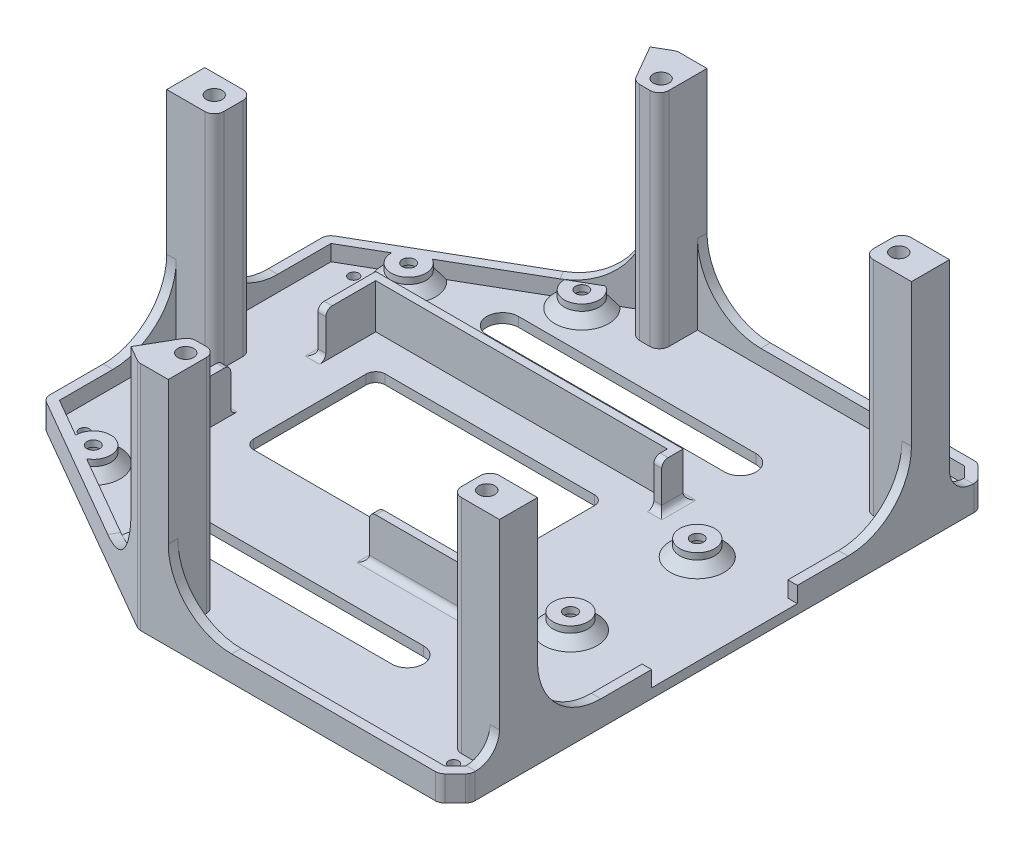
SolidWorks part; units mm, degrees
material "ABS"
ref_plane "Front Plane" through (0, 0, 0) normal (0, 0, 1) x (1, 0, 0)
ref_plane "Top Plane" through (0, 0, 0) normal (0, 1, 0) x (1, 0, 0)
ref_plane "Right Plane" through (0, 0, 0) normal (1, 0, 0) x (0, 0, -1)
sketch "Sketch1" plane through (0, 0, 0) normal (0, 1, 0) x (1, 0, 0)
  line L0 (-50, 85) -> (-120, 44.5855)
  line L1 (-50, -85) -> (50, -85)
  line L2 (-50, -85) -> (-50, 85) construction
  line L3 (-50, 85) -> (50, 85)
  line L4 (50, -85) -> (50, 85)
  line L5 (-50, -85) -> (50, 85) construction
  line L6 (-50, 85) -> (50, -85) construction
  line L7 (-120, 44.5855) -> (-120, -44.5855)
  line L8 (-120, -44.5855) -> (-50, -85)
  line L9 (-120, 0) -> (-35, 0) construction
  line L10 (-85, 64.7927) -> (-47.5919, 0) construction
  line L11 (-47.5919, 0) -> (-85, -64.7927) construction
  circle A0 centre (-35, 0) radius 85 construction
  point P0 (0, 0)
  dimension "D5" = 120
  dimension "D1" = 170
  dimension "D2" = 100
  dimension "D3" = 170
  dimension "D4" = 85
extrude "Boss-Extrude1" add sketch "Sketch1" along normal blind 3
chamfer "Chamfer1" distance 5 angle 45 2 edges at (50, 1.5, 85) (50, 1.5, -85)
fillet "Fillet1" radius 3 8 edges at (50, 1.5, -80) (45, 1.5, -85) (-50, 1.5, -85) (-50, 1.5, 85) (-120, 1.5, -44.5855) (-120, 1.5, 44.5855) (50, 1.5, 80) (45, 1.5, 85)
sketch "Sketch3" plane through (0, 3, 0) normal (0, 1, 0) x (1, 0, 0)
  line L0 (-117, 42.8534) -> (-117, -42.8534)
  line L1 (-117, -42.8534) -> (-49.1962, -82)
  line L2 (-49.1962, -82) -> (43.7574, -82)
  line L3 (43.7574, -82) -> (47, -78.7574)
  line L4 (47, -78.7574) -> (47, 78.7574)
  line L5 (47, 78.7574) -> (43.7574, 82)
  line L6 (43.7574, 82) -> (-49.1962, 82)
  line L7 (-49.1962, 82) -> (-117, 42.8534)
  line L8 (50, -78.7574) -> (50, 78.7574)
  line L9 (49.1213, 80.8787) -> (45.8787, 84.1213)
  line L10 (43.7574, 85) -> (-49.1962, 85)
  line L11 (-50.6962, 84.5981) -> (-118.5, 45.4515)
  line L12 (-120, 42.8534) -> (-120, -42.8534)
  line L13 (-118.5, -45.4515) -> (-50.6962, -84.5981)
  line L14 (-49.1962, -85) -> (43.7574, -85)
  line L15 (45.8787, -84.1213) -> (49.1213, -80.8787)
  line L16 (50, -78.7574) -> (50, 78.7574)
  line L17 (49.1213, 80.8787) -> (45.8787, 84.1213)
  line L18 (43.7574, 85) -> (-49.1962, 85)
  line L19 (-50.6962, 84.5981) -> (-118.5, 45.4515)
  line L20 (-120, 42.8534) -> (-120, -42.8534)
  line L21 (-118.5, -45.4515) -> (-50.6962, -84.5981)
  line L22 (-49.1962, -85) -> (43.7574, -85)
  line L23 (45.8787, -84.1213) -> (49.1213, -80.8787)
  arc A0 (-117, -42.8534) -> (-117, -42.8534) centre (-117, -42.8534) ccw
  arc A1 (-49.1962, -82) -> (-49.1962, -82) centre (-49.1962, -82) ccw
  arc A2 (43.7574, -82) -> (43.7574, -82) centre (43.7574, -82) ccw
  arc A3 (47, -78.7574) -> (47, -78.7574) centre (47, -78.7574) ccw
  arc A4 (47, 78.7574) -> (47, 78.7574) centre (47, 78.7574) ccw
  arc A5 (43.7574, 82) -> (43.7574, 82) centre (43.7574, 82) ccw
  arc A6 (-49.1962, 82) -> (-49.1962, 82) centre (-49.1962, 82) ccw
  arc A7 (-117, 42.8534) -> (-117, 42.8534) centre (-117, 42.8534) ccw
  arc A8 (50, 78.7574) -> (49.1213, 80.8787) centre (47, 78.7574) ccw
  arc A9 (45.8787, 84.1213) -> (43.7574, 85) centre (43.7574, 82) ccw
  arc A10 (-49.1962, 85) -> (-50.6962, 84.5981) centre (-49.1962, 82) ccw
  arc A11 (-118.5, 45.4515) -> (-120, 42.8534) centre (-117, 42.8534) ccw
  arc A12 (-120, -42.8534) -> (-118.5, -45.4515) centre (-117, -42.8534) ccw
  arc A13 (-50.6962, -84.5981) -> (-49.1962, -85) centre (-49.1962, -82) ccw
  arc A14 (43.7574, -85) -> (45.8787, -84.1213) centre (43.7574, -82) ccw
  arc A15 (49.1213, -80.8787) -> (50, -78.7574) centre (47, -78.7574) ccw
  arc A16 (50, 78.7574) -> (49.1213, 80.8787) centre (47, 78.7574) ccw
  arc A17 (45.8787, 84.1213) -> (43.7574, 85) centre (43.7574, 82) ccw
  arc A18 (-49.1962, 85) -> (-50.6962, 84.5981) centre (-49.1962, 82) ccw
  arc A19 (-118.5, 45.4515) -> (-120, 42.8534) centre (-117, 42.8534) ccw
  arc A20 (-120, -42.8534) -> (-118.5, -45.4515) centre (-117, -42.8534) ccw
  arc A21 (-50.6962, -84.5981) -> (-49.1962, -85) centre (-49.1962, -82) ccw
  arc A22 (43.7574, -85) -> (45.8787, -84.1213) centre (43.7574, -82) ccw
  arc A23 (49.1213, -80.8787) -> (50, -78.7574) centre (47, -78.7574) ccw
  dimension "D1" = 0
  dimension "D2" = 3
extrude "Boss-Extrude2" add sketch "Sketch3" along normal blind 5
sketch "Sketch9" plane through (0, 3, 0) normal (0, 1, 0) x (1, 0, 0)
  line L0 (38, 85) -> (38, 76) construction
  line L1 (43.7574, 85) -> (-49.1962, 85) construction
  line L2 (41, 73) -> (50, 73) construction
  line L3 (50, -78.7574) -> (50, 78.7574) construction
  line L4 (50, 73) -> (50, 78.7574) construction
  line L5 (49.1213, 80.8787) -> (45.8787, 84.1213) construction
  line L6 (43.7574, 85) -> (38, 85) construction
  line L7 (-55.3827, 81.8923) -> (-49.3827, 71.5)
  line L8 (-46.7846, 70) -> (-43.5167, 70)
  line L9 (49.1213, 80.8787) -> (45.8787, 84.1213) construction
  line L10 (-120, 38.2457) -> (-108, 38.2457) construction
  line L11 (-120, 42.8534) -> (-120, -42.8534) construction
  line L12 (-105, 41.2457) -> (-105, 53.2457) construction
  line L13 (-50.6962, 84.5981) -> (-118.5, 45.4515) construction
  line L14 (-105, 53.2457) -> (-118.5, 45.4515) construction
  line L15 (-120, 42.8534) -> (-120, 38.2457) construction
  line L16 (-120, 0) -> (50, 0) construction
  line L26 (-40.5167, 73) -> (-40.5167, 85)
  line L27 (43.7574, 85) -> (-49.1962, 85) construction
  line L28 (-40.5167, 85) -> (-49.1962, 85)
  line L29 (-50.6962, 84.5981) -> (-55.3827, 81.8923)
  line L30 (-120, 0) -> (-105, 0)
  line L31 (-105, -3) -> (-105, 3)
  line L32 (-108, 6) -> (-120, 6)
  line L33 (-120, 6) -> (-120, -6)
  line L34 (50, 71) -> (38, 71)
  line L35 (35, 68) -> (35, 62)
  line L36 (38, 59) -> (50, 59)
  line L37 (50, 59) -> (50, 71)
  line L38 (38, -59) -> (50, -59)
  line L39 (35, -68) -> (35, -62)
  line L40 (50, -71) -> (38, -71)
  line L41 (50, -59) -> (50, -71)
  line L42 (-40.5167, -85) -> (-49.1962, -85)
  line L43 (-40.5167, -73) -> (-40.5167, -85)
  line L44 (-46.7846, -70) -> (-43.5167, -70)
  line L45 (-55.3827, -81.8923) -> (-49.3827, -71.5)
  line L46 (-50.6962, -84.5981) -> (-55.3827, -81.8923)
  line L47 (-108, -6) -> (-120, -6)
  arc A0 (-49.1962, 85) -> (-50.6962, 84.5981) centre (-49.1962, 82) ccw
  arc A1 (45.8787, 84.1213) -> (43.7574, 85) centre (43.7574, 82) ccw construction
  arc A2 (50, 78.7574) -> (49.1213, 80.8787) centre (47, 78.7574) ccw construction
  arc A3 (-118.5, 45.4515) -> (-120, 42.8534) centre (-117, 42.8534) ccw construction
  arc A4 (-105, 41.2457) -> (-108, 38.2457) centre (-108, 41.2457) cw construction
  arc A5 (38, 76) -> (41, 73) centre (41, 76) ccw construction
  arc A11 (-43.5167, 70) -> (-40.5167, 73) centre (-43.5167, 73) ccw
  arc A12 (-49.3827, 71.5) -> (-46.7846, 70) centre (-46.7846, 73) ccw
  arc A13 (-105, 3) -> (-108, 6) centre (-108, 3) ccw
  arc A14 (35, 62) -> (38, 59) centre (38, 62) ccw
  arc A15 (38, 71) -> (35, 68) centre (38, 68) ccw
  arc A16 (35, -62) -> (38, -59) centre (38, -62) cw
  arc A17 (38, -71) -> (35, -68) centre (38, -68) cw
  arc A18 (-43.5167, -70) -> (-40.5167, -73) centre (-43.5167, -73) cw
  arc A19 (-49.3827, -71.5) -> (-46.7846, -70) centre (-46.7846, -73) cw
  arc A20 (-49.1962, -85) -> (-50.6962, -84.5981) centre (-49.1962, -82) cw
  arc A21 (-105, -3) -> (-108, -6) centre (-108, -3) cw
  point P19 (45, 85)
  point P30 (-105, 38.2457)
  point P47 (-40.5167, 70)
  point P50 (-48.5167, 70)
  point P53 (-105, 6)
  point P58 (50, 56.4054)
  point P61 (35, 59)
  point P64 (35, 71)
  line M20 (43.7574, 82) -> (-49.1962, 82)
  line M21 (-49.1962, 82) -> (-117, 42.8534)
  line M22 (-117, 42.8534) -> (-117, -42.8534)
  line M23 (-117, -42.8534) -> (-49.1962, -82)
  line M31 (-49.1962, -82) -> (43.7574, -82)
  line M33 (47, -78.7574) -> (47, 78.7574)
  dimension "D2" = 3
  dimension "D3" = 3
  dimension "D4" = 3
  dimension "D6" = 3
  dimension "D7" = 3
  dimension "D10" = 3
  dimension "D11" = 3
  dimension "D14" = 3
  dimension "D18" = 3
  dimension "D1" = 12
  dimension "D5" = 15
  dimension "D8" = 15
  dimension "D9" = 8
  dimension "D12" = 6
  dimension "D13" = 15
  dimension "D15" = 12
  dimension "D16" = 15
  dimension "D17" = 14
extrude "Boss-Extrude5" add sketch "Sketch9" along normal blind 70 contours L31 A13 L32 L30 M22 | A21 L31 L30 L47 M22 | A19 L45 L43 A18 L44 M23 M31 | A20 L42 L43 L45 L46 M31 M23 | A17 L40 L38 A16 L39 M33 | L41 L38 L40 M33 | L32 L33 L30 M22 | L47 L30 L33 M22 | L7 A12 L8 A11 L26 M20 M21 | L28 A0 L29 L7 L26 M21 M20 | L34 A15 L35 A14 L36 M33 | L36 L37 L34 M33
fillet "Fillet2" radius 20 8 edges at (-54.6327, 8, -80.5933) (-40.5167, 8, -83.5) (48.5, 8, -59) (48.5, 8, 59) (-40.5167, 8, 83.5) (-54.6327, 8, 80.5933) (-118.5, 8, -6) (-118.5, 8, 6)
fillet "Fillet4" radius 7.5 2 edges at (48.5, 8, -71) (48.5, 8, 71)
sketch "Sketch10" plane through (0, 3, 0) normal (0, 1, 0) x (1, 0, 0)
  line L0 (0, 0) -> (39.5, 0) construction
  line L1 (0, 0) -> (-109.5, 0) construction
  line L2 (-109.5, -42.5) -> (-109.5, 42.5) construction
  line L3 (39.5, -75) -> (39.5, 75) construction
  line L4 (-109.5, 42.5) -> (39.5, 75) construction
  line L5 (-109.5, -42.5) -> (39.5, -75) construction
  circle A0 centre (-109.5, 42.5) radius 1.6
  circle A1 centre (-109.5, -42.5) radius 1.6
  circle A2 centre (39.5, -75) radius 1.6
  circle A3 centre (39.5, 75) radius 1.6
  point P7 (-109.5, 0)
  point P10 (39.5, 0)
  dimension "D5" = 3.2
  dimension "D1" = 39.5
  dimension "D2" = 150
  dimension "D3" = 149
  dimension "D4" = 85
extrude "Cut-Extrude1" cut sketch "Sketch10" against normal blind 10
sketch "Sketch11" plane through (0, 0, 0) normal (0, -1, 0) x (1, 0, 0)
  line L0 (-120, 0) -> (-47.59, 0) construction
  line L1 (-120, -42.8534) -> (-120, 42.8534) construction
  line L2 (-47.59, 0) -> (-82.09, 59.7558) construction
  line L3 (-47.59, 0) -> (-82.09, -59.7558) construction
  line L4 (-47.59, 0) -> (21.41, 0) construction
  line L11 (-99.4105, 49.7558) -> (-64.7695, 69.7558) construction
  line L12 (21.41, -20) -> (21.41, 20) construction
  line L13 (-99.4105, -49.7558) -> (-64.7695, -69.7558) construction
  circle A0 centre (-99.4105, 49.7558) radius 2.5
  circle A1 centre (-64.7695, 69.7558) radius 2.5
  circle A2 centre (-99.4105, -49.7558) radius 2.5
  circle A3 centre (-64.7695, -69.7558) radius 2.5
  circle A4 centre (21.41, -20) radius 2.5
  circle A5 centre (21.41, 20) radius 2.5
  point P12 (21.41, 0)
  point P20 (-82.09, -59.7558)
  dimension "D6" = 5
  dimension "D1" = 69
  dimension "D2" = 72.41
  dimension "D3" = 120
  dimension "D4" = 120
  dimension "D5" = 40
extrude "Cut-Extrude2" cut sketch "Sketch11" against normal blind 20
sketch "Sketch12" plane through (0, 3, 0) normal (0, 1, 0) x (1, 0, 0)
  circle A0 centre (-99.4105, -49.7558) radius 2.5 construction
  circle A1 centre (-64.7695, -69.7558) radius 2.5 construction
  circle A2 centre (21.41, -20) radius 2.5 construction
  circle A3 centre (21.41, 20) radius 2.5 construction
  circle A4 centre (-64.7695, 69.7558) radius 2.5 construction
  circle A5 centre (-99.4105, 49.7558) radius 2.5 construction
  circle A6 centre (-99.4105, -49.7558) radius 2.5
  circle A7 centre (-64.7695, -69.7558) radius 2.5
  circle A8 centre (21.41, -20) radius 2.5
  circle A9 centre (21.41, 20) radius 2.5
  circle A10 centre (-64.7695, 69.7558) radius 2.5
  circle A11 centre (-99.4105, 49.7558) radius 2.5
  circle A12 centre (-99.4105, -49.7558) radius 5.5
  circle A13 centre (-64.7695, -69.7558) radius 5.5
  circle A14 centre (21.41, -20) radius 5.5
  circle A15 centre (21.41, 20) radius 5.5
  circle A16 centre (-64.7695, 69.7558) radius 5.5
  circle A17 centre (-99.4105, 49.7558) radius 5.5
  dimension "D1" = 3
extrude "Boss-Extrude6" add sketch "Sketch12" along normal blind 3
sketch "Sketch13" plane through (0, 6, 0) normal (0, 1, 0) x (1, 0, 0)
  line L0 (-70.2689, -69.8336) -> (-62.0872, -74.5573) construction
  line L1 (-62.0872, 74.5573) -> (-70.2689, 69.8336) construction
  line L2 (-96.7282, 54.5573) -> (-104.91, 49.8336) construction
  line L3 (-104.91, -49.8336) -> (-96.7282, -54.5573) construction
  line L4 (-70.2689, -69.8336) -> (-62.0872, -74.5573)
  line L5 (-62.0872, 74.5573) -> (-70.2689, 69.8336)
  line L6 (-96.7282, 54.5573) -> (-104.91, 49.8336)
  line L7 (-104.91, -49.8336) -> (-96.7282, -54.5573)
  arc A0 (-62.0872, -74.5573) -> (-70.2689, -69.8336) centre (-64.7695, -69.7558) ccw construction
  circle A1 centre (21.41, -20) radius 5.5 construction
  arc A2 (-70.2689, 69.8336) -> (-62.0872, 74.5573) centre (-64.7695, 69.7558) ccw construction
  arc A3 (-104.91, 49.8336) -> (-96.7282, 54.5573) centre (-99.4105, 49.7558) ccw construction
  arc A4 (-96.7282, -54.5573) -> (-104.91, -49.8336) centre (-99.4105, -49.7558) ccw construction
  circle A5 centre (21.41, 20) radius 5.5 construction
  arc A6 (-62.0872, -74.5573) -> (-70.2689, -69.8336) centre (-64.7695, -69.7558) ccw
  circle A7 centre (21.41, -20) radius 5.5
  arc A8 (-70.2689, 69.8336) -> (-62.0872, 74.5573) centre (-64.7695, 69.7558) ccw
  arc A9 (-104.91, 49.8336) -> (-96.7282, 54.5573) centre (-99.4105, 49.7558) ccw
  arc A10 (-96.7282, -54.5573) -> (-104.91, -49.8336) centre (-99.4105, -49.7558) ccw
  circle A11 centre (21.41, 20) radius 5.5
  circle A12 centre (-99.4105, 49.7558) radius 2
  circle A13 centre (-64.7695, 69.7558) radius 2
  circle A14 centre (21.41, 20) radius 2
  circle A15 centre (21.41, -20) radius 2
  circle A16 centre (-99.4105, -49.7558) radius 2
  circle A17 centre (-64.7695, -69.7558) radius 2
  dimension "D1" = 4
extrude "Boss-Extrude7" add sketch "Sketch13" along normal blind 2
chamfer "Chamfer2" distance 3 angle 45 6 edges at (-96.6605, 3, 44.9926) (-62.0195, 3, 64.9926) (21.41, 3, 14.5) (21.41, 3, -25.5) (-96.6605, 3, -44.9926) (-62.0195, 3, -64.9926)
sketch "Sketch14" plane through (0, 73, 0) normal (0, 1, 0) x (1, 0, 0)
  line L0 (40, 65) -> (40, -65) construction
  line L1 (0, 0) -> (40, 0) construction
  line L2 (40, 65) -> (-45, 75) construction
  line L3 (-45, 75) -> (-111, 0) construction
  line L4 (-111, 0) -> (-45, -75) construction
  line L5 (-45, -75) -> (40, -65) construction
  circle A0 centre (-111, 0) radius 2.5
  circle A1 centre (-45, 75) radius 2.5
  circle A2 centre (40, 65) radius 2.5
  circle A3 centre (40, -65) radius 2.5
  circle A4 centre (-45, -75) radius 2.5
  point P3 (40, 0)
  dimension "D7" = 5
  dimension "D1" = 40
  dimension "D2" = 130
  dimension "D3" = 85
  dimension "D4" = 75
  dimension "D5" = 66
  dimension "D6" = 10
extrude "Cut-Extrude3" cut sketch "Sketch14" against normal blind 6
sketch "Sketch15" plane through (0, 67, 0) normal (0, 1, 0) x (1, 0, 0)
  circle A0 centre (-111, 0) radius 2
  circle A1 centre (-45, 75) radius 2
  circle A2 centre (40, 65) radius 2
  circle A3 centre (40, -65) radius 2
  circle A4 centre (-45, -75) radius 2
  dimension "D1" = 4
extrude "Cut-Extrude4" cut sketch "Sketch15" against normal blind 20
sketch "Sketch16" plane through (0, 3, 0) normal (0, 1, 0) x (1, 0, 0)
  line L0 (-111, 0) -> (-90.795, 0) construction
  line L1 (-90.795, -30.75) -> (1.205, -30.75)
  line L2 (-90.795, -30.75) -> (-90.795, 30.75)
  line L3 (-90.795, 30.75) -> (1.205, 30.75)
  line L4 (1.205, -30.75) -> (1.205, 30.75)
  line L5 (-90.795, -30.75) -> (1.205, 30.75) construction
  line L6 (-90.795, 30.75) -> (1.205, -30.75) construction
  line L7 (21.41, 20) -> (21.41, -20) construction
  line L8 (1.205, 0) -> (21.41, 0) construction
  line L9 (-93.295, 33.25) -> (3.705, 33.25)
  line L10 (3.705, -33.25) -> (3.705, 33.25)
  line L11 (-93.295, -33.25) -> (3.705, -33.25)
  line L12 (-93.295, -33.25) -> (-93.295, 33.25)
  line L14 (-3.705, -26.5) -> (3.705, -26.5)
  line L15 (-3.705, -26.5) -> (-3.705, 26.5)
  line L16 (-3.705, 26.5) -> (3.705, 26.5)
  line L17 (3.705, -26.5) -> (3.705, 26.5)
  line L18 (-3.705, -26.5) -> (3.705, 26.5) construction
  line L19 (-3.705, 26.5) -> (3.705, -26.5) construction
  line L21 (-83.795, -28.25) -> (-28.795, -28.25)
  line L22 (-83.795, -28.25) -> (-83.795, -33.25)
  line L23 (-83.795, -33.25) -> (-28.795, -33.25)
  line L24 (-28.795, -28.25) -> (-28.795, -33.25)
  line L25 (-83.795, -28.25) -> (-28.795, -33.25) construction
  line L26 (-83.795, -33.25) -> (-28.795, -28.25) construction
  line L27 (-88.295, -15) -> (-93.295, -15)
  line L28 (-88.295, -15) -> (-88.295, 15)
  line L29 (-88.295, 15) -> (-93.295, 15)
  line L30 (-93.295, -15) -> (-93.295, 15)
  line L31 (-88.295, -15) -> (-93.295, 15) construction
  line L32 (-88.295, 15) -> (-93.295, -15) construction
  point P0 (-44.795, 0)
  point P19 (0, 0)
  point P24 (-93.295, -16.7268)
  point P27 (-56.295, -30.75)
  dimension "D1" = 61.5
  dimension "D2" = 92
  dimension "D3" = 2.5
  dimension "D4" = 53
  dimension "D5" = 7
  dimension "D6" = 55
  dimension "D7" = 30
extrude "Boss-Extrude8" add sketch "Sketch16" along normal blind 14 contours L29 L2 L3 L4 L16 L10 L9 L12 | L2 L27 L12 L11 L22 L1 | L1 L24 L11 L10 L14 L4
fillet "Fillet5" radius 2 19 edges at (-93.295, 3, -24.125) (-44.795, 3, -33.25) (3.705, 3, -29.875) (-93.295, 3, 24.125) (-88.545, 3, 33.25) (3.705, 3, 29.875) (-12.545, 3, 33.25) (2.455, 17, -26.5) (2.455, 3, -26.5) (-92.045, 3, -15) (-92.045, 17, -15) (2.455, 3, 26.5) (2.455, 17, 26.5) (-28.795, 17, 32) (-28.795, 3, 32) (-92.045, 3, 15) (-92.045, 17, 15) (-83.795, 17, 32) (-83.795, 3, 32)
sketch "Sketch17" plane through (0, 3, 0) normal (0, 1, 0) x (1, 0, 0)
  line L0 (1.205, 30.75) -> (-90.795, -30.75) construction
  line L1 (-90.795, 17) -> (-90.795, 30.75) construction
  line L2 (-11.795, -20.75) -> (-77.795, -20.75)
  line L3 (-8.795, -17.75) -> (-8.795, 17.75)
  line L4 (-11.795, 20.75) -> (-77.795, 20.75)
  line L5 (-80.795, -17.75) -> (-80.795, 17.75)
  line L6 (-8.795, -20.75) -> (-80.795, 20.75) construction
  line L7 (-8.795, 20.75) -> (-80.795, -20.75) construction
  line L8 (-90.795, 30.75) -> (1.205, 30.75) construction
  arc A0 (-77.795, -20.75) -> (-80.795, -17.75) centre (-77.795, -17.75) cw
  arc A1 (-11.795, -20.75) -> (-8.795, -17.75) centre (-11.795, -17.75) ccw
  arc A2 (-8.795, 17.75) -> (-11.795, 20.75) centre (-11.795, 17.75) ccw
  arc A3 (-77.795, 20.75) -> (-80.795, 17.75) centre (-77.795, 17.75) ccw
  point P4 (-44.795, 0)
  dimension "D3" = 3
  dimension "D1" = 10
  dimension "D2" = 10
extrude "Cut-Extrude5" cut sketch "Sketch17" against normal blind 15 contours L3 A2 L4 A3 L5 A0 L2 A1
sketch "Sketch18" plane through (0, 3, 0) normal (0, 1, 0) x (1, 0, 0)
  line L0 (-120, 0) -> (50, 0) construction
  line L1 (-120, 6) -> (-120, -6) construction
  line L2 (50, -39) -> (50, 39) construction
  line L3 (-35, -52.5) -> (-35, 52.5) construction
  line L4 (-72.5, 52.5) -> (2.5, 52.5) construction
  line L5 (-72.5, 57.5) -> (2.5, 57.5)
  line L6 (-72.5, 47.5) -> (2.5, 47.5)
  line L7 (-72.5, -52.5) -> (2.5, -52.5) construction
  line L9 (-72.5, -47.5) -> (2.5, -47.5)
  line L10 (-72.5, -57.5) -> (2.5, -57.5)
  arc A0 (-72.5, 57.5) -> (-72.5, 47.5) centre (-72.5, 52.5) ccw
  arc A1 (2.5, 47.5) -> (2.5, 57.5) centre (2.5, 52.5) ccw
  arc A2 (-72.5, -47.5) -> (-72.5, -57.5) centre (-72.5, -52.5) ccw
  arc A3 (2.5, -57.5) -> (2.5, -47.5) centre (2.5, -52.5) ccw
  point P9 (-35, 0)
  point P11 (-35, 52.5)
  point P20 (-35, -52.5)
  dimension "D1" = 105
  dimension "D2" = 10
  dimension "D3" = 75
  dimension "D4" = 10
  dimension "D5" = 75
extrude "Cut-Extrude6" cut sketch "Sketch18" against normal blind 15
sketch "Sketch19" plane through (0, 3, 0) normal (0, 1, 0) x (1, 0, 0)
  line L0 (47, -59) -> (47, 59) construction
  line L1 (42, -23) -> (52, -23)
  line L2 (42, -23) -> (42, 23)
  line L3 (42, 23) -> (52, 23)
  line L4 (52, -23) -> (52, 23)
  line L5 (42, -23) -> (52, 23) construction
  line L6 (42, 23) -> (52, -23) construction
  point P0 (47, 0)
  dimension "D1" = 46
  dimension "D2" = 10
extrude "Cut-Extrude7" cut sketch "Sketch19" along normal blind 20
